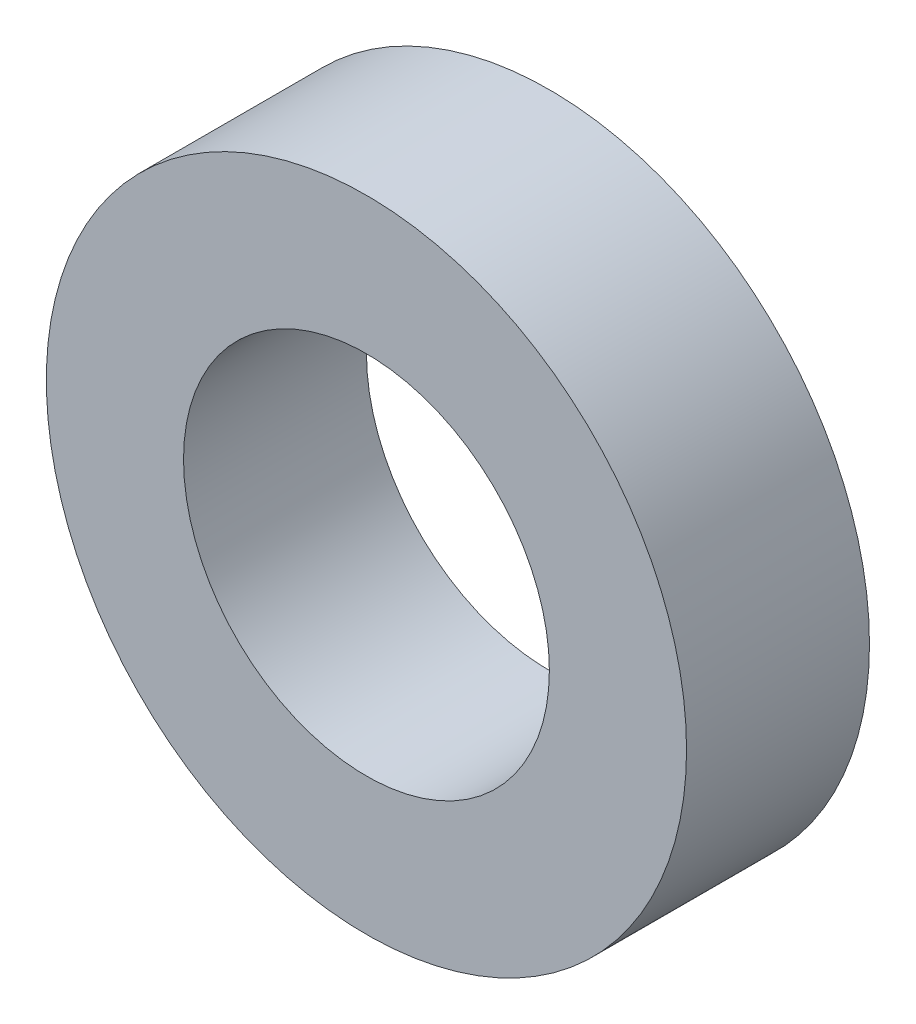
SolidWorks part; units mm, degrees
ref_plane "前视基准面" through (0, 0, 0) normal (0, 0, 1) x (1, 0, 0)
ref_plane "上视基准面" through (0, 0, 0) normal (0, 1, 0) x (1, 0, 0)
ref_plane "右视基准面" through (0, 0, 0) normal (1, 0, 0) x (0, 0, -1)
sketch "草图1" plane through (0, 0, 0) normal (0, 0, 1) x (1, 0, 0)
  circle A0 centre (0, 0) radius 10
  circle A1 centre (0, 0) radius 17.5
  dimension "D1" = 20
  dimension "D2" = 35
extrude "凸台-拉伸1" add sketch "草图1" along normal blind 10
